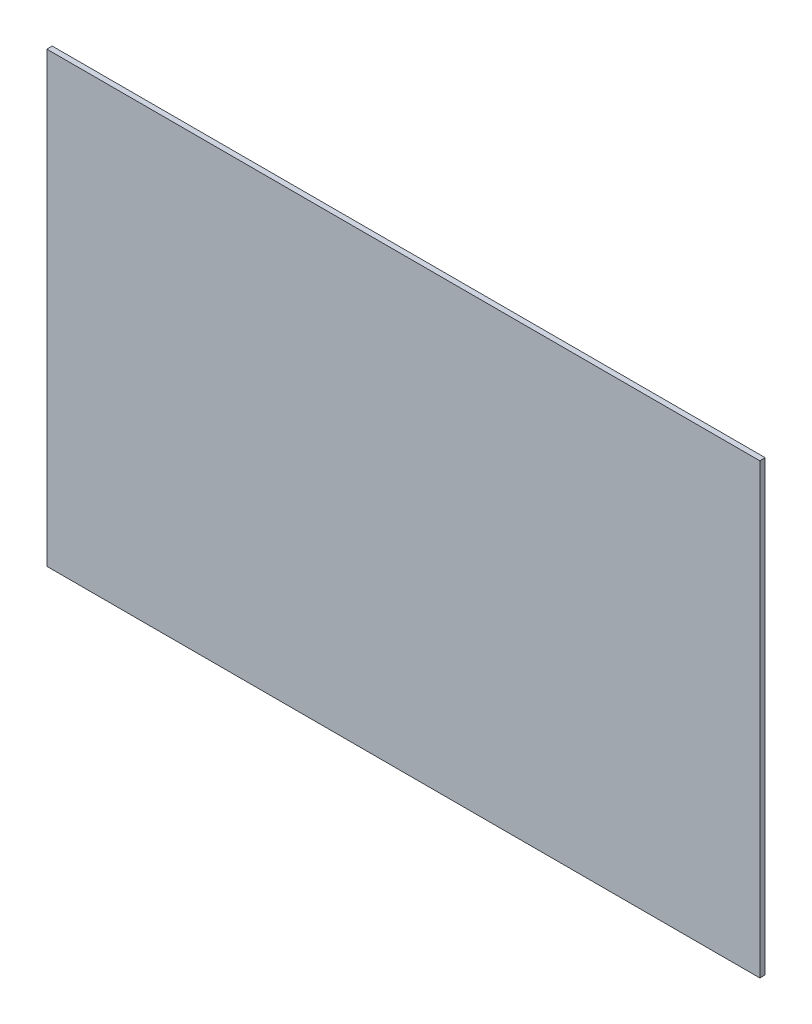
SolidWorks part; units mm, degrees
ref_plane "Front Plane" through (0, 0, 0) normal (0, 0, 1) x (1, 0, 0)
ref_plane "Top Plane" through (0, 0, 0) normal (0, 1, 0) x (1, 0, 0)
ref_plane "Right Plane" through (0, 0, 0) normal (1, 0, 0) x (0, 0, -1)
sketch "Sketch1" plane through (0, 0, 0) normal (0, 0, 1) x (1, 0, 0)
  line L1 (0, 0) -> (-398, 0)
  line L2 (0, 0) -> (0, 250)
  line L3 (0, 250) -> (-398, 250)
  line L4 (-398, 0) -> (-398, 250)
  dimension "D1" = 250
  dimension "D2" = 398
extrude "Boss-Extrude1" add sketch "Sketch1" along normal blind 3
